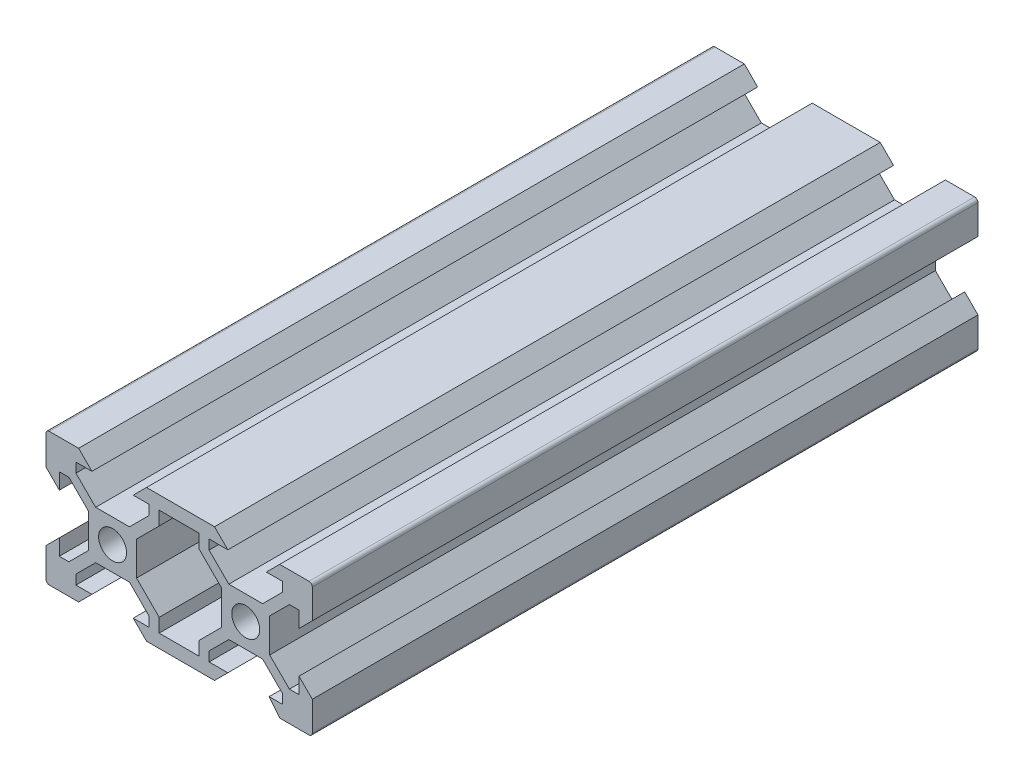
SolidWorks part; units mm, degrees
material "6063-T5"
ref_plane "Front Plane" through (0, 0, 0) normal (0, 0, 1) x (1, 0, 0)
ref_plane "Top Plane" through (0, 0, 0) normal (0, 1, 0) x (1, 0, 0)
ref_plane "Right Plane" through (0, 0, 0) normal (1, 0, 0) x (0, 0, -1)
sketch "Sketch1" plane through (0, 0, 0) normal (0, 0, 1) x (1, 0, 0)
  line L0 (-26.1395, 0) -> (11.0607, 0) construction
  line L1 (0, -20.0817) -> (0, 17.1243) construction
  line L2 (-20, 10.7318) -> (-20, -11.6858) construction
  line L3 (20, 11.8444) -> (20, -11.2237) construction
  line L4 (-23.1467, 10) -> (24.2381, 10) construction
  line L5 (23.8217, -10) -> (-26.7834, -10) construction
  line L6 (3, -5.9393) -> (3, -8)
  line L7 (-20, -10) -> (-15.5, -10)
  line L8 (-20, -10) -> (-20, -5.5)
  line L9 (-18, -5.5) -> (-16.5607, -5.5)
  line L10 (-15.5, -8) -> (-15.5, -6.5607)
  line L11 (-20, 10) -> (-15.5, 10)
  line L12 (-20, 10) -> (-20, 5.5)
  line L13 (-18, 5.5) -> (-16.5607, 5.5)
  line L14 (-15.5, 8) -> (-15.5, 6.5607)
  line L15 (20, 10) -> (15.5, 10)
  line L16 (20, 10) -> (20, 5.5)
  line L17 (18, 5.5) -> (16.5607, 5.5)
  line L18 (15.5, 8) -> (15.5, 6.5607)
  line L19 (20, -10) -> (15.5, -10)
  line L20 (20, -10) -> (20, -5.5)
  line L21 (18, -5.5) -> (16.5607, -5.5)
  line L22 (15.5, -8) -> (15.5, -6.5607)
  line L23 (4.5, -6.5607) -> (4.5, -8)
  line L24 (12.5393, 3.6) -> (15.5, 6.5607)
  line L25 (7.4607, -3.6) -> (4.5, -6.5607)
  line L27 (-4.5, 8) -> (-6.9, 8)
  line L28 (-12.5393, -3.6) -> (-15.5, -6.5607)
  line L29 (7.4607, 3.6) -> (4.5, 6.5607)
  line L30 (12.5393, -3.6) -> (15.5, -6.5607)
  line L31 (-13.6, -2.5393) -> (-16.5607, -5.5)
  line L32 (-13.6, 2.5393) -> (-16.5607, 5.5)
  line L33 (6.4, -2.5393) -> (3, -5.9393)
  line L34 (20, 5.5) -> (20, 5.1)
  line L35 (20, 5.1) -> (18, 3.1)
  line L36 (18, 3.1) -> (18, 5.5)
  line L37 (20, -5.5) -> (20, -5.1)
  line L38 (20, -5.1) -> (18, -3.1)
  line L39 (18, -3.1) -> (18, -5.5)
  line L40 (15.5, 10) -> (15.1, 10)
  line L41 (15.1, 10) -> (13.1, 8)
  line L42 (13.1, 8) -> (15.5, 8)
  line L43 (15.5, -10) -> (15.1, -10)
  line L44 (15.1, -10) -> (13.5138, -8)
  line L45 (13.5138, -8) -> (15.5, -8)
  line L46 (-15.5, 10) -> (-15.1, 10)
  line L47 (-15.1, 10) -> (-13.1, 8)
  line L48 (-13.1, 8) -> (-15.5, 8)
  line L49 (-20, 5.5) -> (-20, 5.1)
  line L50 (-20, 5.1) -> (-18, 3.1)
  line L51 (-18, 3.1) -> (-18, 5.5)
  line L52 (-20, -5.5) -> (-20, -5.1)
  line L53 (-20, -5.1) -> (-18, -3.1)
  line L54 (-18, -3.1) -> (-18, -5.5)
  line L55 (-15.5, -10) -> (-15.1, -10)
  line L56 (-15.1, -10) -> (-13.1, -8)
  line L57 (-13.1, -8) -> (-15.5, -8)
  line L58 (6.4, 2.5393) -> (3, 5.9393)
  line L59 (3, 8) -> (-3, 8)
  line L61 (-3, 5.9393) -> (-3, 8)
  line L62 (-12.5393, 3.6) -> (-15.5, 6.5607)
  line L63 (-4.5, 6.5607) -> (-4.5, 8)
  line L64 (4.5, 6.5607) -> (4.5, 8)
  line L65 (3, 5.9393) -> (3, 8)
  line L66 (13.6, 2.5393) -> (16.5607, 5.5)
  line L67 (12.1, 0) -> (30.0509, 0) construction
  line L68 (-7.4607, 3.6) -> (-4.5, 6.5607)
  line L69 (3, -8) -> (-3, -8)
  line L70 (-6.4, 2.5393) -> (-3, 5.9393)
  line L71 (13.6, -2.5393) -> (16.5607, -5.5)
  line L73 (-3, -5.9393) -> (-3, -8)
  line L74 (-4.5, -6.5607) -> (-4.5, -8)
  line L75 (-7.4607, -3.6) -> (-4.5, -6.5607)
  line L76 (-6.4, -2.5393) -> (-3, -5.9393)
  line L77 (5.3138, -10) -> (7.3138, -8)
  line L78 (7.3138, -8) -> (4.5, -8)
  line L79 (-6.9, -8) -> (-4.9, -10)
  line L80 (-4.9, -10) -> (5.3138, -10)
  line L81 (5.3138, 10) -> (7.3138, 8)
  line L82 (-4.9, 10) -> (5.3138, 10)
  line L83 (-6.9, 8) -> (-4.9, 10)
  line L84 (7.3138, 8) -> (4.5, 8)
  line L85 (7.4607, -3.6) -> (12.5393, -3.6)
  line L86 (-7.4607, -3.6) -> (-12.5393, -3.6)
  line L87 (-6.4, -2.5393) -> (-6.4, 2.5393)
  line L88 (-7.4607, 3.6) -> (-12.5393, 3.6)
  line L89 (-13.6, -2.5393) -> (-13.6, 2.5393)
  line L90 (6.4, -2.5393) -> (6.4, 2.5393)
  line L91 (13.6, -2.5393) -> (13.6, 2.5393)
  line L92 (7.4607, 3.6) -> (12.5393, 3.6)
  line L93 (-4.5, -8) -> (-6.9, -8)
  circle A0 centre (-10, 0) radius 2.1
  circle A1 centre (10, 0) radius 2.1
  dimension "D2" = 4.2
  dimension "D5" = 45
  dimension "D6" = 45
  dimension "D7" = 6.2
  dimension "D8" = 6.2
  dimension "D11" = 3.6
  dimension "D12" = 3.6
  dimension "D38" = 2.4
  dimension "D39" = 45
  dimension "D40" = 2.4
  dimension "D41" = 45
  dimension "D42" = 2
  dimension "D43" = 45
  dimension "D44" = 2.4
  dimension "D45" = 2
  dimension "D49" = 11
extrude "Boss-Extrude1" add sketch "Sketch1" along normal blind 100
fillet "Fillet1" radius 0.5 4 edges at (-20, -10, 50) (-20, 10, 50) (20, -10, 50) (20, 10, 50)
